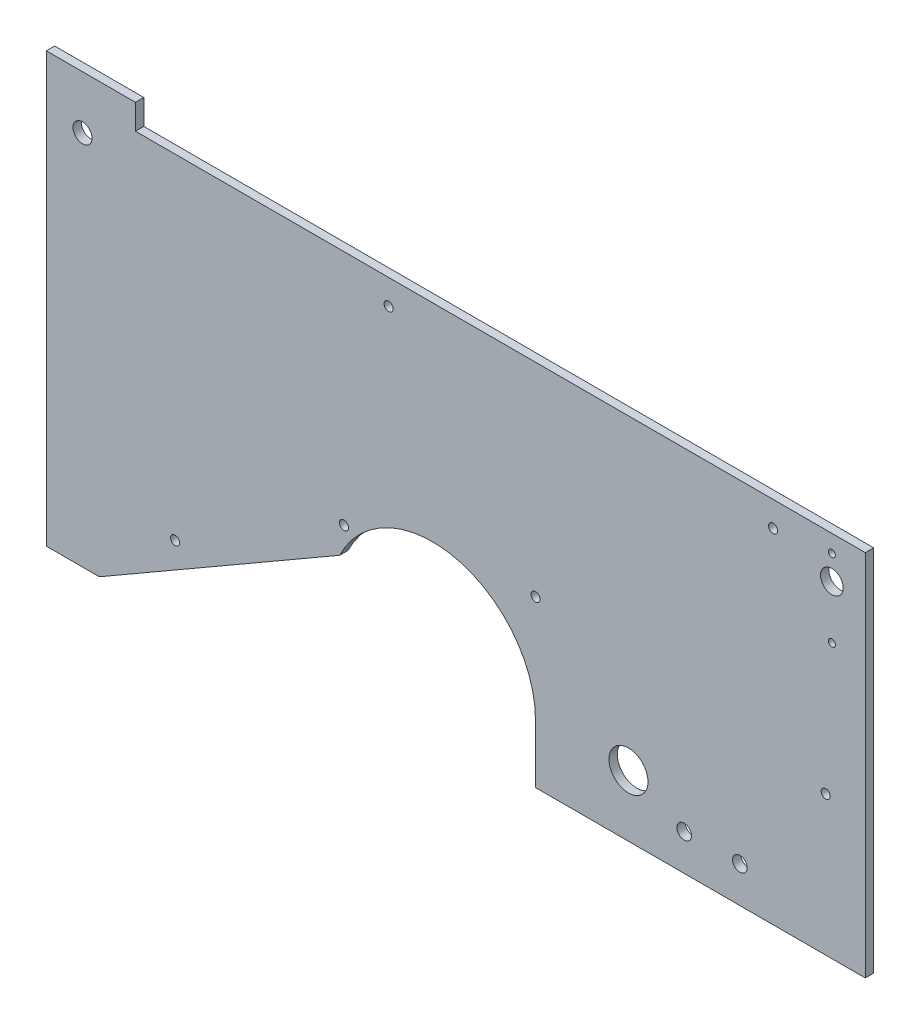
SolidWorks part; units mm, degrees
ref_plane "Front Plane" through (0, 0, 0) normal (0, 0, 1) x (1, 0, 0)
ref_plane "Top Plane" through (0, 0, 0) normal (0, 1, 0) x (1, 0, 0)
ref_plane "Right Plane" through (0, 0, 0) normal (1, 0, 0) x (0, 0, -1)
sketch "Sketch2" plane through (0, 0, 0) normal (0, 0, 1) x (1, 0, 0)
  line L0 (25.0304, 0) -> (111.2865, 49.8)
  line L1 (0, 0) -> (25.0304, 0)
  line L2 (0, 0) -> (0, 154)
  line L4 (300, 0) -> (300, 145)
  line L5 (181.6, 33.7) -> (181.6, 0)
  line L6 (181.6, 0) -> (300, 0)
  line L7 (19, 135) -> (19, 164.3674) construction
  line L11 (38, 145) -> (300, 145)
  line L12 (0, 154) -> (19, 154)
  line L13 (19, 154) -> (38, 154)
  line L14 (38, 154) -> (38, 145)
  line L15 (19, 135) -> (50019, 135) construction
  line L20 (19, 135) -> (19, -49865) construction
  circle A0 centre (19, 135) radius 3.425
  arc A1 (181.6, 33.7) -> (111.2865, 49.8) centre (144.6, 33.7) ccw
  point P19 (19, 154)
  dimension "D3" = 135
  dimension "D4" = 19
  dimension "D5" = 6.85
  dimension "D6" = 74
  dimension "D7" = 155.4
  dimension "D8" = 33.7
  dimension "D1" = 300
  dimension "D2" = 154
  dimension "D9" = 30
  dimension "D10" = 99.6
  dimension "D11" = 19
extrude "Boss-Extrude2" add sketch "Sketch2" along normal blind 3
sketch "Sketch3" plane through (0, 0, 3) normal (0, 0, 1) x (1, 0, 0)
  line L0 (300, 0) -> (300, 145) construction
  line L1 (181.6, 0) -> (300, 0)
  line L2 (181.6, 0) -> (181.6, 12.75)
  line L3 (181.6, 12.75) -> (300, 12.75)
  line L4 (300, 0) -> (300, 12.75)
  dimension "D1" = 12.75
extrude "Cut-Extrude1" cut sketch "Sketch3" against normal through all
sketch "Sketch4" plane through (0, 0, 3) normal (0, 0, 1) x (1, 0, 0)
  line L0 (19, 135) -> (19, -49865) construction
  line L1 (19, 135) -> (-49981, 135) construction
sketch "Sketch5" plane through (0, 0, 3) normal (0, 0, 1) x (1, 0, 0)
  line L0 (300, 12.75) -> (300, 145) construction
  line L1 (300, 12.75) -> (181.6, 12.75) construction
  line L2 (300, 145) -> (38, 145) construction
  line L3 (0, 154) -> (0, 0) construction
  line L4 (0, 0) -> (25.0304, 0) construction
  line L6 (0, 154) -> (6, 154)
  line L7 (0, 154) -> (0, 0)
  line L8 (0, 0) -> (6, 0)
  line L9 (6, 154) -> (6, 0)
  circle A0 centre (254.98, 25.75) radius 2.625
  circle A1 centre (234.98, 25.75) radius 2.625
  circle A2 centre (288, 130) radius 4.075
  circle A3 centre (288, 138.75) radius 1.25
  circle A4 centre (288, 110.95) radius 1.25
  circle A5 centre (181.6, 72.03) radius 1.625
  circle A6 centre (285.78, 62.92) radius 1.625
  circle A7 centre (52.23, 24.91) radius 1.625
  circle A8 centre (112.84, 59.93) radius 1.625
  circle A9 centre (266.89, 135.99) radius 1.625
  circle A10 centre (128.89, 135.99) radius 1.625
  circle A11 centre (214.98, 34.75) radius 7
  dimension "D1" = 5.25
  dimension "D2" = 45.02
  dimension "D3" = 13
  dimension "D4" = 5.25
  dimension "D5" = 20
  dimension "D6" = 13
  dimension "D9" = 8.15
  dimension "D10" = 2.5
  dimension "D11" = 8.75
  dimension "D12" = 12
  dimension "D13" = 27.8
  dimension "D14" = 12
  dimension "D15" = 2.5
  dimension "D16" = 3.25
  dimension "D17" = 118.4
  dimension "D18" = 72.97
  dimension "D19" = 3.25
  dimension "D20" = 14.22
  dimension "D21" = 82.08
  dimension "D22" = 52.23
  dimension "D23" = 3.25
  dimension "D24" = 24.91
  dimension "D25" = 112.84
  dimension "D26" = 3.25
  dimension "D27" = 59.93
  dimension "D28" = 9.01
  dimension "D29" = 3.25
  dimension "D30" = 33.11
  dimension "D31" = 3.25
  dimension "D32" = 9.01
  dimension "D33" = 138
  dimension "D35" = 22
  dimension "D36" = 20
  dimension "D37" = 14
  dimension "D7" = 12
  dimension "D8" = 15
  dimension "D34" = 6
extrude "Cut-Extrude2" cut sketch "Sketch5" against normal through all
